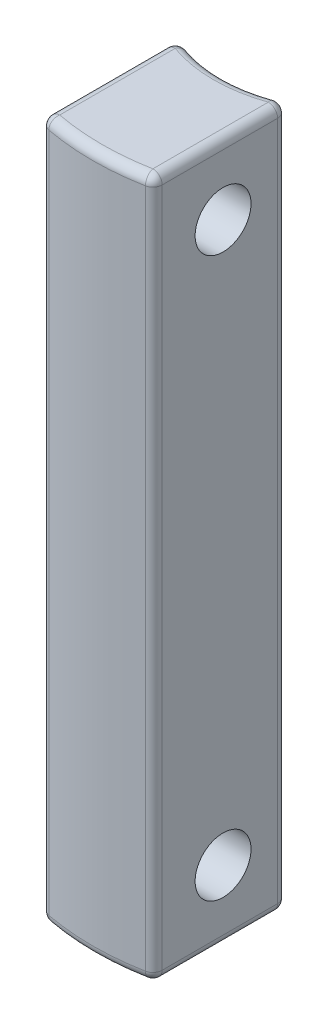
SolidWorks part; units mm, degrees
ref_plane "前视基准面" through (0, 0, 0) normal (0, 0, 1) x (1, 0, 0)
ref_plane "上视基准面" through (0, 0, 0) normal (0, 1, 0) x (1, 0, 0)
ref_plane "右视基准面" through (0, 0, 0) normal (1, 0, 0) x (0, 0, -1)
other "Configuration Table"
sketch "草图1" plane through (0, 0, 0) normal (0, 1, 0) x (1, 0, 0)
  line L0 (-22.5406, 0) -> (34.25, 0) construction
  line L1 (0, 36.1528) -> (0, -39.0802) construction
  line L2 (-6, -7.3502) -> (-6, 7.3502)
  line L4 (6, -7.3502) -> (6, 7.3502)
  arc A0 (-6, -7.3502) -> (6, -7.3502) centre (0, 19.9993) ccw
  arc A1 (6, 7.3502) -> (-6, 7.3502) centre (0, 19.9993) cw
  point P11 (0, 5.9993)
  point P12 (0, -8.0007)
  point P13 (0, 0)
  point P14 (0, 0)
  point P15 (0, 0)
  point P16 (0, 0)
  point P17 (0, 0)
  point P18 (0, 0)
  point P19 (0, 0)
  point P20 (0, 0)
  dimension "D1" = 14
  dimension "D2" = 28
  dimension "D3" = 14
  dimension "D4" = 12
extrude "凸台-拉伸1" add sketch "草图1" along normal mid plane 75
sketch "草图2" plane through (0, 0, 0) normal (1, 0, 0) x (0, 0, -1)
  line L0 (0, 31.8292) -> (0, -28.5029) construction
  line L1 (-5.4393, 0) -> (5.4544, 0) construction
  circle A0 centre (0, 30) radius 3
  circle A1 centre (0, -30) radius 3
  dimension "D2" = 6
  dimension "D1" = 60
extrude "切除-拉伸1" cut sketch "草图2" against normal through all both and the other way through all
fillet "圆角2" radius 1 12 edges at (6, 0, -7.3502) (-6, 0, -7.3502) (6, -37.5, 0) (0, -37.5, -5.9993) (-6, -37.5, 0) (-6, 37.5, 0) (0, 37.5, -5.9993) (6, 37.5, 0) (-6, 0, 7.3502) (0, 37.5, 8.0007) (6, 0, 7.3502) (0, -37.5, 8.0007)
